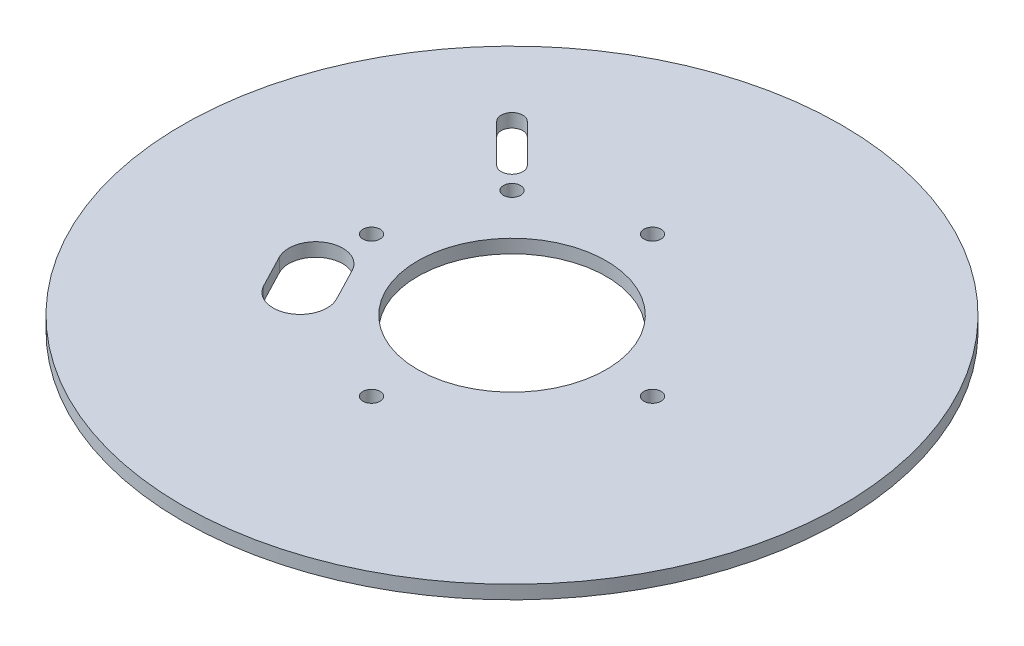
SolidWorks part; units mm, degrees
material "Acrylic (Medium-high impact)"
ref_plane "Front" through (0, 0, 0) normal (0, 0, 1) x (1, 0, 0)
ref_plane "Top" through (0, 0, 0) normal (0, 1, 0) x (1, 0, 0)
ref_plane "Right" through (0, 0, 0) normal (1, 0, 0) x (0, 0, -1)
sketch "Sketch1" plane through (0, 0, 0) normal (0, 1, 0) x (1, 0, 0)
  circle A0 centre (0, 0) radius 77.46
  dimension "D1" = 154.92
extrude "Boss-Extrude1" add sketch "Sketch1" along normal blind 3.175
sketch "Sketch24" plane through (0, 3.175, 0) normal (0, 1, 0) x (1, 0, 0)
  line L0 (-30.48, 30.48) -> (-39.4603, 39.4603) construction
  line L1 (-32.2761, 28.6839) -> (-41.2563, 37.6642)
  line L2 (-28.6839, 32.2761) -> (-37.6642, 41.2563)
  line L3 (-33.5359, -12.5897) -> (-29.5483, -20.2499) construction
  line L4 (-27.9034, -9.6576) -> (-23.9158, -17.3178)
  line L5 (-39.1685, -15.5218) -> (-35.1808, -23.182)
  line L6 (0, 0) -> (22.86, 0) construction
  line L7 (-33.5359, -12.5897) -> (0, 0) construction
  line L8 (0, 0) -> (-29.5483, -20.2499) construction
  line L9 (-31.5421, -16.4198) -> (0, 0) construction
  circle A0 centre (0, 0) radius 22.1615
  circle A1 centre (0, 0) radius 33.02 construction
  circle A2 centre (-25.4, 25.4) radius 2.0193
  circle A3 centre (0, 33.02) radius 2.0193
  circle A4 centre (33.02, 0) radius 2.0193
  circle A5 centre (0, -33.02) radius 2.0193
  circle A6 centre (-33.02, 0) radius 2.0193
  arc A7 (-32.2761, 28.6839) -> (-28.6839, 32.2761) centre (-30.48, 30.48) ccw
  arc A8 (-37.6642, 41.2563) -> (-41.2563, 37.6642) centre (-39.4603, 39.4603) ccw
  arc A9 (-27.9034, -9.6576) -> (-39.1685, -15.5218) centre (-33.5359, -12.5897) ccw
  arc A10 (-35.1808, -23.182) -> (-23.9158, -17.3178) centre (-29.5483, -20.2499) ccw
  point P16 (-34.9701, 34.9701)
  point P21 (-31.5421, -16.4198)
  dimension "D1" = 4.0386
  dimension "D4" = 44.323
  dimension "D10" = 2.54
  dimension "D14" = 6.35
  dimension "D2" = 25.4
  dimension "D3" = 25.4
  dimension "D5" = 33.02
  dimension "D6" = 27.5
  dimension "D7" = 45
  dimension "D8" = 30.48
  dimension "D9" = 30.48
  dimension "D11" = 12.7
  dimension "D12" = 35.56
  dimension "D13" = 8.636
extrude "Cut-Extrude14" cut sketch "Sketch24" against normal through all
